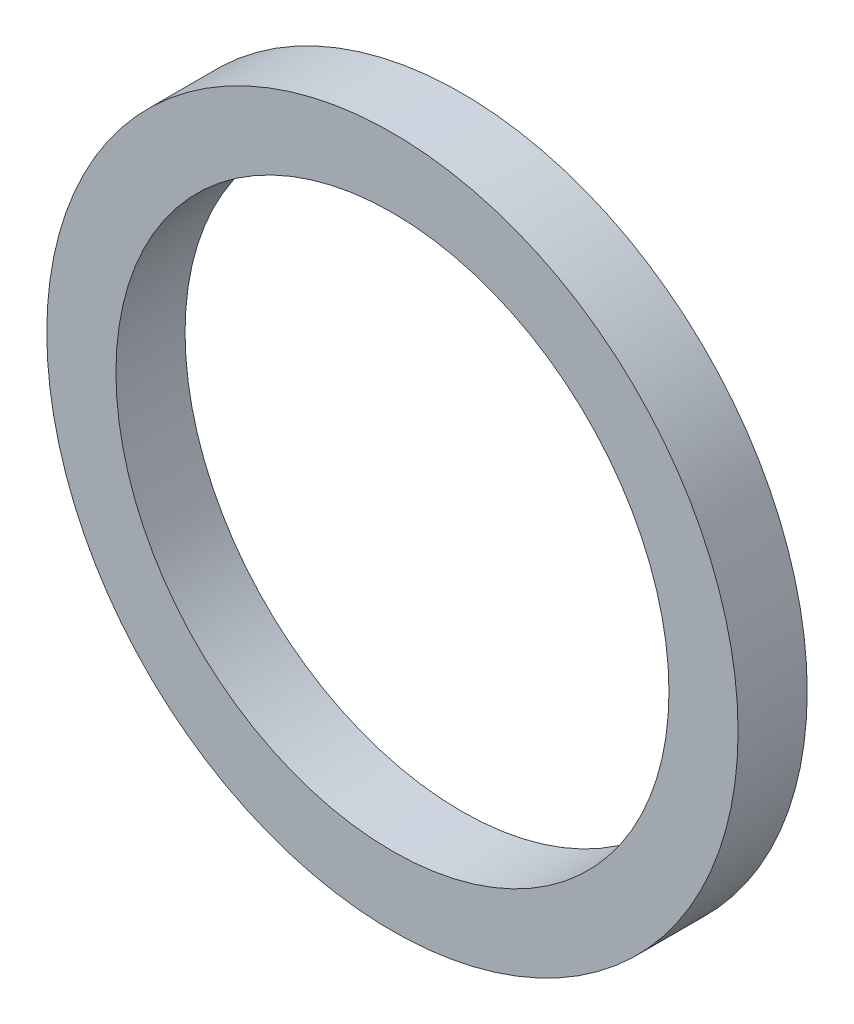
SolidWorks part; units mm, degrees
material "Custom Plastic"
ref_plane "Front Plane" through (0, 0, 0) normal (0, 0, 1) x (1, 0, 0)
ref_plane "Top Plane" through (0, 0, 0) normal (0, 1, 0) x (1, 0, 0)
ref_plane "Right Plane" through (0, 0, 0) normal (1, 0, 0) x (0, 0, -1)
sketch "Sketch1" plane through (0, 0, 0) normal (0, 0, 1) x (1, 0, 0)
  circle A0 centre (0, 0) radius 75
  circle A1 centre (0, 0) radius 60
extrude "Boss-Extrude1" add sketch "Sketch1" along normal blind 15
